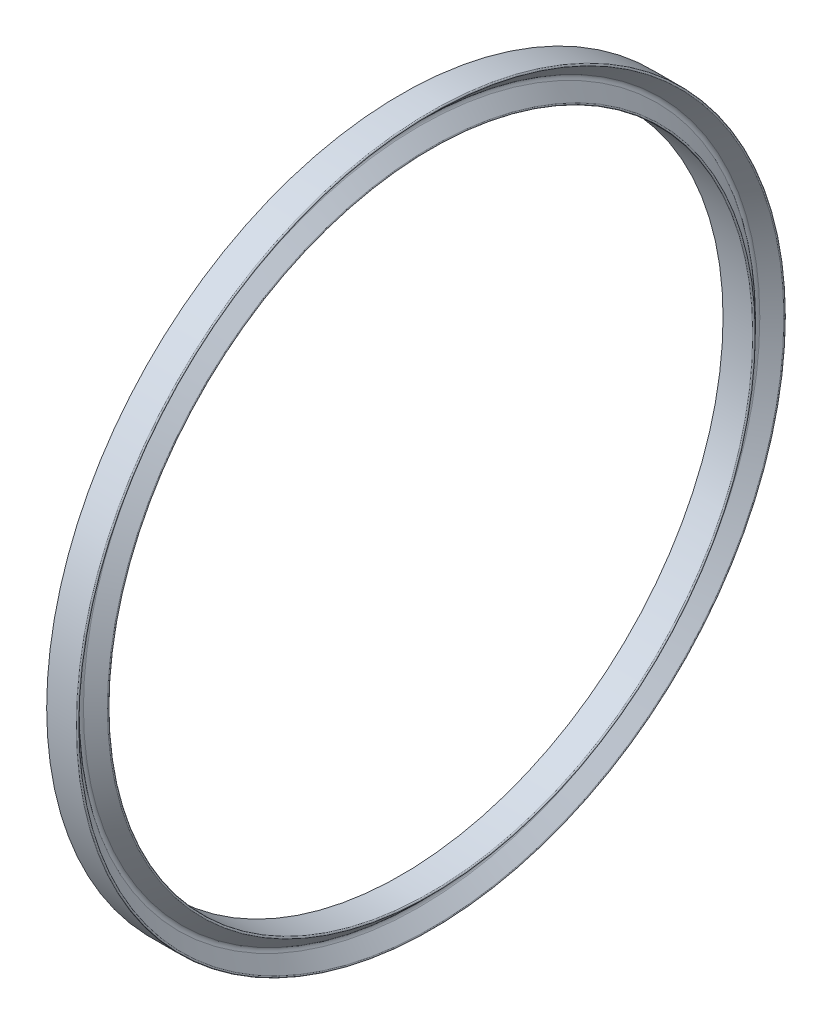
SolidWorks part; units mm, degrees
material "PP Copolymer"
ref_plane "Ön Düzlem" through (0, 0, 0) normal (0, 0, 1) x (1, 0, 0)
ref_plane "Üst Düzlem" through (0, 0, 0) normal (0, 1, 0) x (1, 0, 0)
ref_plane "Sağ Düzlem" through (0, 0, 0) normal (1, 0, 0) x (0, 0, -1)
sketch "Sketch1" plane through (0, 0, 0) normal (0, 0, 1) x (1, 0, 0)
  line L0 (-76.3248, 0) -> (84.0344, 0) construction
  line L1 (-58.5482, -33) -> (-55.7896, -33)
  line L2 (-58.5482, -30) -> (-55.7896, -30)
  line L3 (-58.5482, -30) -> (-58.5482, -33)
  line L4 (-58.5482, -30) -> (-55.5482, -33) construction
  line L5 (-55.5482, -30) -> (-58.5482, -33) construction
  line L6 (-58.5482, -33) -> (-58.4516, -33.0405) construction
  line L7 (-55.7189, -30.1707) -> (-56.836, -31.2879)
  line L8 (-56.836, -31.7121) -> (-55.7189, -32.8293)
  arc A0 (-56.836, -31.2879) -> (-56.836, -31.7121) centre (-56.6239, -31.5) ccw
  arc A1 (-55.7189, -32.8293) -> (-55.7896, -33) centre (-55.7896, -32.9) cw
  arc A2 (-55.7189, -30.1707) -> (-55.7896, -30) centre (-55.7896, -30.1) ccw
  point P11 (-57.0482, -31.5)
  dimension "D5" = 0.3
  dimension "D6" = 0.1
  dimension "D1" = 33
  dimension "D2" = 30
  dimension "D3" = 3
  dimension "D4" = 3
revolve "Revolve1" add sketch "Sketch1" angle 360 about L0
